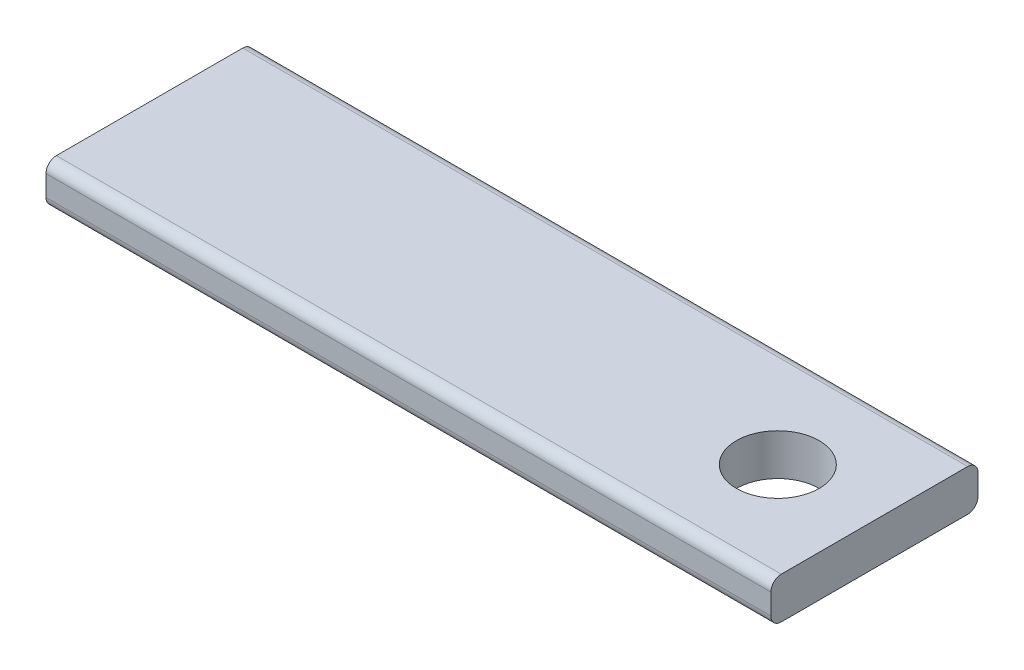
SolidWorks part; units mm, degrees
ref_plane "正面" through (0, 0, 0) normal (0, 0, 1) x (1, 0, 0)
ref_plane "平面" through (0, 0, 0) normal (0, 1, 0) x (1, 0, 0)
ref_plane "右側面" through (0, 0, 0) normal (1, 0, 0) x (0, 0, -1)
sketch "ｽｹｯﾁ1" plane through (0, 0, 0) normal (0, 1, 0) x (1, 0, 0)
  line L1 (-26.25, -7.5) -> (26.25, -7.5)
  line L2 (-26.25, -7.5) -> (-26.25, 7.5)
  line L3 (-26.25, 7.5) -> (26.25, 7.5)
  line L4 (26.25, -7.5) -> (26.25, 7.5)
  line L5 (-26.25, -7.5) -> (26.25, 7.5) construction
  line L6 (-26.25, 7.5) -> (26.25, -7.5) construction
  point P0 (0, 0)
  dimension "D1" = 15
  dimension "D2" = 52.5
extrude "ﾎﾞｽ - 押し出し1" add sketch "ｽｹｯﾁ1" along normal mid plane 3
fillet "ﾌｨﾚｯﾄ1" radius 0.75 4 edges at (0, -1.5, -7.5) (0, 1.5, -7.5) (0, -1.5, 7.5) (0, 1.5, 7.5)
sketch "ｽｹｯﾁ2" plane through (0, 1.5, 0) normal (0, 1, 0) x (1, 0, 0)
  line L0 (26.25, 0) -> (19.25, 0) construction
  line L1 (26.25, -6.75) -> (26.25, 6.75) construction
  circle A0 centre (19.25, 0) radius 3
  dimension "D2" = 6
  dimension "D1" = 7
extrude "ｶｯﾄ - 押し出し1" cut sketch "ｽｹｯﾁ2" against normal blind 3
